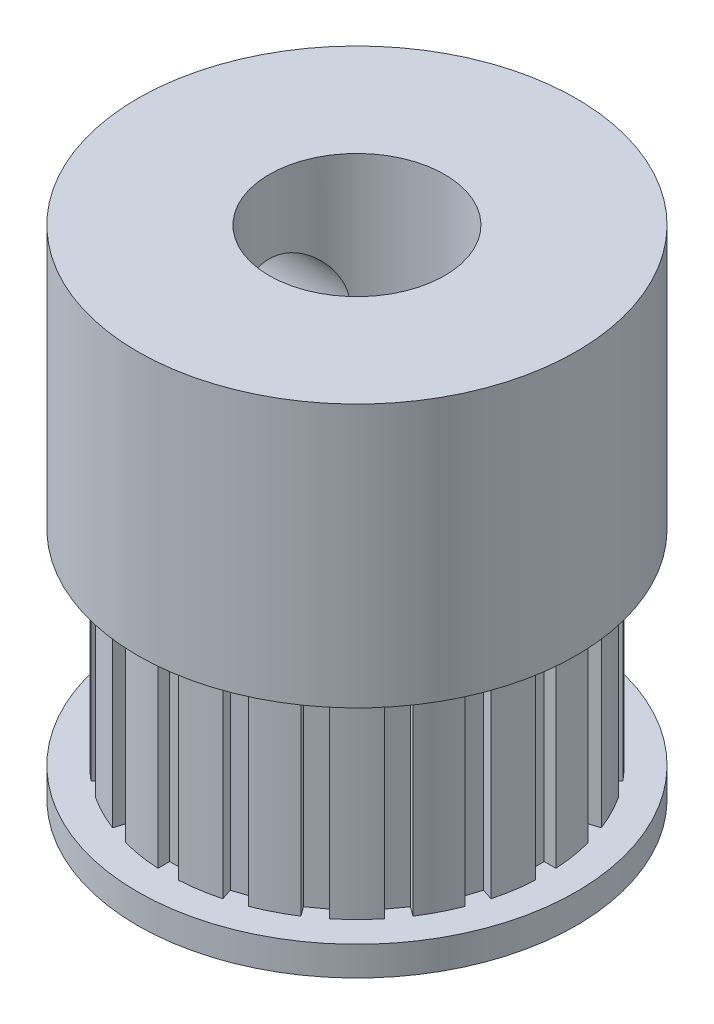
SolidWorks part; units mm, degrees
ref_plane "前视" through (0, 0, 0) normal (0, 0, 1) x (1, 0, 0)
ref_plane "上视" through (0, 0, 0) normal (0, 1, 0) x (1, 0, 0)
ref_plane "右视" through (0, 0, 0) normal (1, 0, 0) x (0, 0, -1)
sketch "草图1" plane through (0, 0, 0) normal (0, 1, 0) x (1, 0, 0)
  circle A0 centre (0, 0) radius 7.5
  dimension "D1" = 15
extrude "凸台-拉伸1" add sketch "草图1" along normal blind 1
sketch "草图2" plane through (0, 1, 0) normal (0, 1, 0) x (1, 0, 0)
  line L0 (-0.35, 6.4555) -> (-0.35, 6.0555)
  line L1 (0.35, 6.4555) -> (0.35, 6.0555)
  line L2 (0.35, 6.0555) -> (-0.35, 6.0555)
  line L3 (1.662, 6.2477) -> (1.5384, 5.8673)
  line L4 (2.2041, 5.651) -> (1.5384, 5.8673)
  line L5 (2.3277, 6.0314) -> (2.2041, 5.651)
  line L6 (3.5113, 5.4283) -> (3.2762, 5.1047)
  line L7 (3.8425, 4.6933) -> (3.2762, 5.1047)
  line L8 (4.0776, 5.0169) -> (3.8425, 4.6933)
  line L9 (5.0169, 4.0776) -> (4.6933, 3.8425)
  line L10 (5.1047, 3.2762) -> (4.6933, 3.8425)
  line L11 (5.4283, 3.5113) -> (5.1047, 3.2762)
  line L12 (6.0314, 2.3277) -> (5.651, 2.2041)
  line L13 (5.8673, 1.5384) -> (5.651, 2.2041)
  line L14 (6.2477, 1.662) -> (5.8673, 1.5384)
  line L15 (6.4555, 0.35) -> (6.0555, 0.35)
  line L16 (6.0555, -0.35) -> (6.0555, 0.35)
  line L17 (6.4555, -0.35) -> (6.0555, -0.35)
  line L18 (6.2477, -1.662) -> (5.8673, -1.5384)
  line L19 (5.651, -2.2041) -> (5.8673, -1.5384)
  line L20 (6.0314, -2.3277) -> (5.651, -2.2041)
  line L21 (5.4283, -3.5113) -> (5.1047, -3.2762)
  line L22 (4.6933, -3.8425) -> (5.1047, -3.2762)
  line L23 (5.0169, -4.0776) -> (4.6933, -3.8425)
  line L24 (4.0776, -5.0169) -> (3.8425, -4.6933)
  line L25 (3.2762, -5.1047) -> (3.8425, -4.6933)
  line L26 (3.5113, -5.4283) -> (3.2762, -5.1047)
  line L27 (2.3277, -6.0314) -> (2.2041, -5.651)
  line L28 (1.5384, -5.8673) -> (2.2041, -5.651)
  line L29 (1.662, -6.2477) -> (1.5384, -5.8673)
  line L30 (0.35, -6.4555) -> (0.35, -6.0555)
  line L31 (-0.35, -6.0555) -> (0.35, -6.0555)
  line L32 (-0.35, -6.4555) -> (-0.35, -6.0555)
  line L33 (-1.662, -6.2477) -> (-1.5384, -5.8673)
  line L34 (-2.2041, -5.651) -> (-1.5384, -5.8673)
  line L35 (-2.3277, -6.0314) -> (-2.2041, -5.651)
  line L36 (-3.5113, -5.4283) -> (-3.2762, -5.1047)
  line L37 (-3.8425, -4.6933) -> (-3.2762, -5.1047)
  line L38 (-4.0776, -5.0169) -> (-3.8425, -4.6933)
  line L39 (-5.0169, -4.0776) -> (-4.6933, -3.8425)
  line L40 (-5.1047, -3.2762) -> (-4.6933, -3.8425)
  line L41 (-5.4283, -3.5113) -> (-5.1047, -3.2762)
  line L42 (-6.0314, -2.3277) -> (-5.651, -2.2041)
  line L43 (-5.8673, -1.5384) -> (-5.651, -2.2041)
  line L44 (-6.2477, -1.662) -> (-5.8673, -1.5384)
  line L45 (-6.4555, -0.35) -> (-6.0555, -0.35)
  line L46 (-6.0555, 0.35) -> (-6.0555, -0.35)
  line L47 (-6.4555, 0.35) -> (-6.0555, 0.35)
  line L48 (-6.2477, 1.662) -> (-5.8673, 1.5384)
  line L49 (-5.651, 2.2041) -> (-5.8673, 1.5384)
  line L50 (-6.0314, 2.3277) -> (-5.651, 2.2041)
  line L51 (-5.4283, 3.5113) -> (-5.1047, 3.2762)
  line L52 (-4.6933, 3.8425) -> (-5.1047, 3.2762)
  line L53 (-5.0169, 4.0776) -> (-4.6933, 3.8425)
  line L54 (-4.0776, 5.0169) -> (-3.8425, 4.6933)
  line L55 (-3.2762, 5.1047) -> (-3.8425, 4.6933)
  line L56 (-3.5113, 5.4283) -> (-3.2762, 5.1047)
  line L57 (-2.3277, 6.0314) -> (-2.2041, 5.651)
  line L58 (-1.5384, 5.8673) -> (-2.2041, 5.651)
  line L59 (-1.662, 6.2477) -> (-1.5384, 5.8673)
  circle A0 centre (0, 0) radius 6.465
  point P85 (0, 0)
  dimension "D1" = 12.93
  dimension "D2" = 0.35
  dimension "D3" = 0.7
  dimension "D4" = 0.4
  dimension "D5" = 20
extrude "凸台-拉伸2" add sketch "草图2" along normal blind 7 contours L30 A0 L29 L28 L27 L26 L25 L24 L23 L22 L21 L20 L19 L18 L17 L16 L15 L14 L13 L12 L11 L10 L9 L8 L7 L6 L5 L4 L3 L1 L2 L0 L59 L58 L57 L56 L55 L54 L53
sketch "草图3" plane through (0, 8, 0) normal (0, 1, 0) x (1, 0, 0)
  circle A0 centre (0, 0) radius 7.5
  dimension "D1" = 15
extrude "凸台-拉伸3" add sketch "草图3" along normal blind 9
sketch "草图4" plane through (0, 17, 0) normal (0, 1, 0) x (1, 0, 0)
  circle A0 centre (0, 0) radius 3
  dimension "D1" = 6
extrude "切除-拉伸1" cut sketch "草图4" against normal up to next
sketch "草图5" plane through (0, 0, 0) normal (1, 0, 0) x (0, 0, -1)
  line L0 (7.5, 17) -> (-7.5, 17) construction
  circle A0 centre (0, 12.5) radius 2
  dimension "D1" = 4
  dimension "D2" = 4.5
extrude "切除-拉伸2" cut sketch "草图5" against normal up to next contours A0
cosmetic thread "装饰螺纹线1" parameters "D2"=4.5
